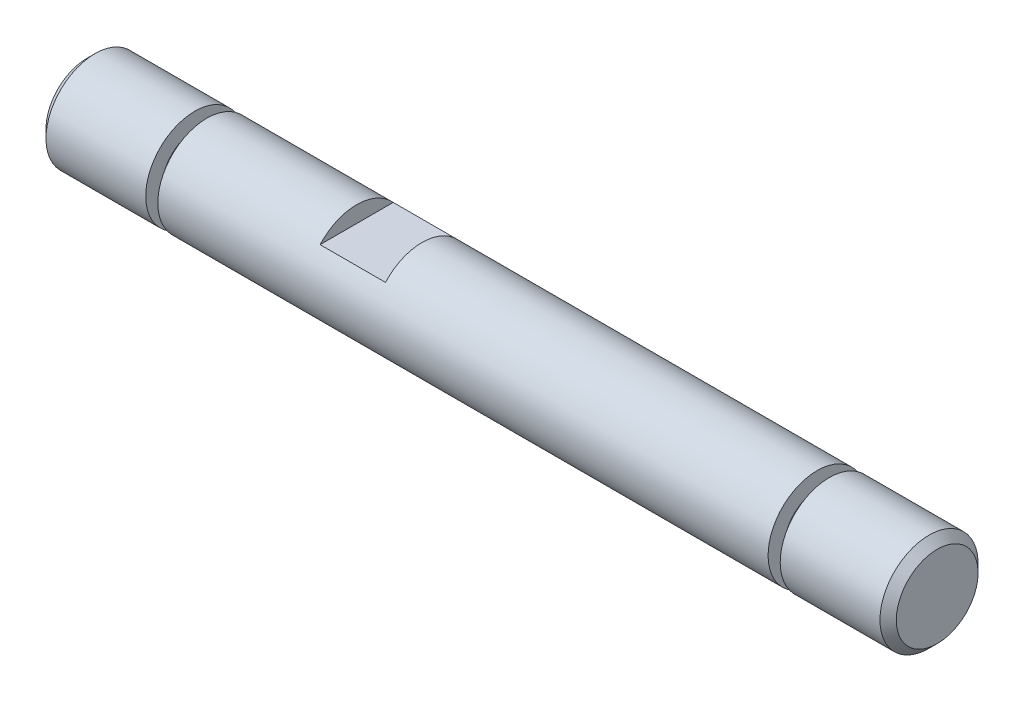
SolidWorks part; units mm, degrees
ref_plane "Plan de face" through (0, 0, 0) normal (0, 0, 1) x (1, 0, 0)
ref_plane "Plan de dessus" through (0, 0, 0) normal (0, 1, 0) x (1, 0, 0)
ref_plane "Plan de droite" through (0, 0, 0) normal (1, 0, 0) x (0, 0, -1)
sketch "Esquisse1" plane through (0, 0, 0) normal (0, 0, 1) x (1, 0, 0)
  line L0 (0, 0) -> (12.8037, 0) construction
  line L1 (0, 0) -> (0, 15.5366) construction
  line L2 (26, 0) -> (-26, 0)
  line L4 (-26, 0) -> (-26, 3)
  line L5 (-26, 3) -> (26, 3)
  line L6 (26, 0) -> (26, 3)
  point P10 (0, 0)
  dimension "D1" = 52
  dimension "D2" = 3
revolve "Révolution1" add sketch "Esquisse1" angle 360 about L0
chamfer "Chanfrein1" distance 0.5 angle 45 2 edges at (-26, 0, 3) (26, 0, 3)
sketch "Esquisse2" plane through (0, 0, 0) normal (0, 0, 1) x (1, 0, 0)
  line L0 (25.5, 3) -> (-25.5, 3) construction
  line L1 (25.5, 3) -> (-25.5, 3)
  line L3 (-9.5, 4) -> (-5.5, 4)
  line L4 (-9.5, 4) -> (-9.5, 2)
  line L5 (-9.5, 2) -> (-5.5, 2)
  line L6 (-5.5, 4) -> (-5.5, 2)
  line L7 (-9.5, 4) -> (-5.5, 2) construction
  line L8 (-9.5, 2) -> (-5.5, 4) construction
  point P2 (-7.5, 3)
  dimension "D1" = 1
  dimension "D2" = 7.5
  dimension "D3" = 4
extrude "Enlèv. mat.-Extru.1" cut sketch "Esquisse2" against normal through all both and the other way through all contours L5 L6 L3 L4
sketch "Esquisse3" plane through (0, 0, 0) normal (0, 0, 1) x (1, 0, 0)
  line L2 (-9.5, 3) -> (-25.5, 3) construction
  line L3 (-19.4, 3) -> (-18.66, 3)
  line L4 (0, 0) -> (0, 10.3249) construction
  line L5 (-19.4, 3) -> (-19.4, 2)
  line L6 (-19.4, 2) -> (-18.66, 2)
  line L7 (-18.66, 3) -> (-18.66, 2)
  line L8 (18.66, 3) -> (18.66, 2)
  line L9 (19.4, 2) -> (18.66, 2)
  line L10 (19.4, 3) -> (19.4, 2)
  line L11 (19.4, 3) -> (18.66, 3)
  line L17 (0, 0) -> (-35.8372, 0) construction
  dimension "D1" = 0.74
  dimension "D2" = 2
  dimension "D3" = 38.8
revolve "Enlèvement de matière-Révolution1" cut sketch "Esquisse3" angle 360 about L17
